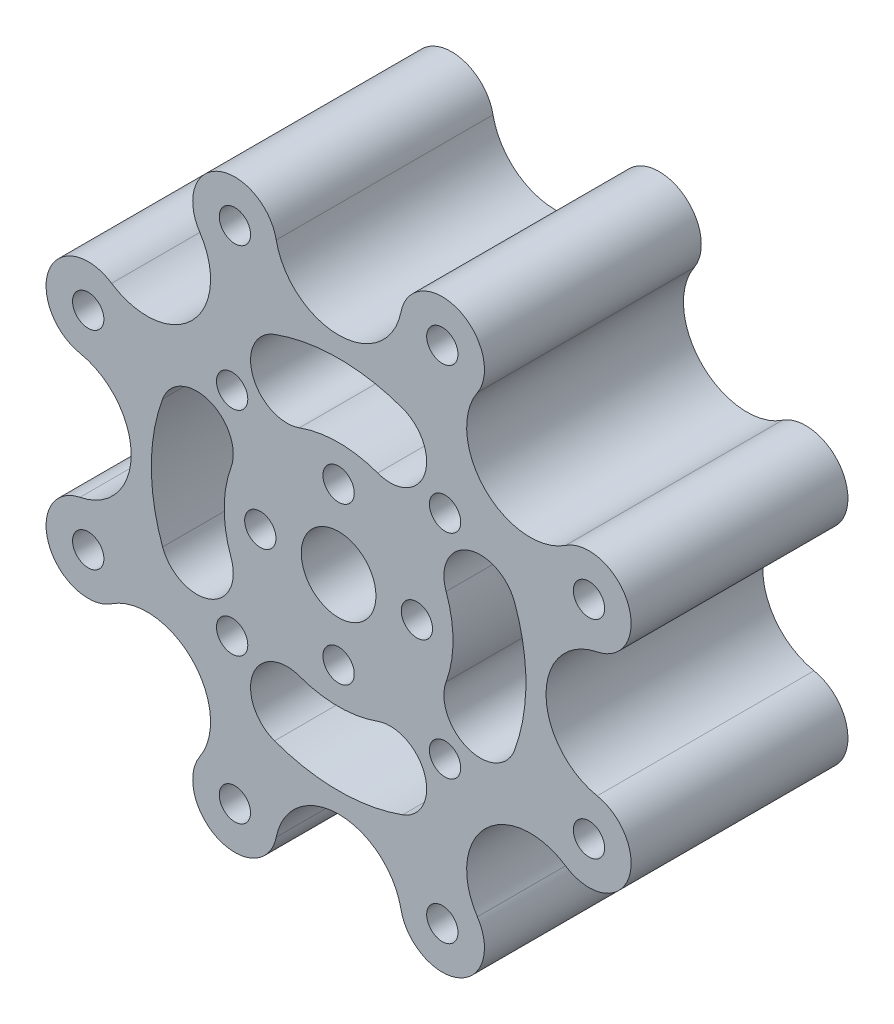
SolidWorks part; units mm, degrees
material "5052-H34"
ref_plane "正面" through (0, 0, 0) normal (0, 0, 1) x (1, 0, 0)
ref_plane "平面" through (0, 0, 0) normal (0, 1, 0) x (1, 0, 0)
ref_plane "右側面" through (0, 0, 0) normal (1, 0, 0) x (0, 0, -1)
sketch "ｽｹｯﾁ1" plane through (0, 0, 0) normal (0, 0, 1) x (1, 0, 0)
  line L0 (0, 27.5) -> (0, 0) construction
  line L1 (0, 0) -> (8.6104, 20.7873) construction
  line L3 (-8.8388, 8.8388) -> (8.8388, 8.8388) construction
  line L4 (-8.8388, 8.8388) -> (-8.8388, -8.8388) construction
  line L5 (-8.8388, -8.8388) -> (8.8388, -8.8388) construction
  line L6 (8.8388, 8.8388) -> (8.8388, -8.8388) construction
  line L7 (-8.8388, 8.8388) -> (8.8388, -8.8388) construction
  line L8 (-8.8388, -8.8388) -> (8.8388, 8.8388) construction
  circle A0 centre (0, 0) radius 27.5
  circle A1 centre (0, 0) radius 22.5 construction
  circle A2 centre (8.6104, 20.7873) radius 1.3
  arc A3 (11.5205, 18.8428) -> (5.1776, 21.4701) centre (8.6104, 20.7873) ccw
  arc A4 (-5.1776, 21.4701) -> (5.1776, 21.4701) centre (0, 22.5) ccw
  circle A5 centre (20.7873, 8.6104) radius 1.3
  circle A6 centre (20.7873, -8.6104) radius 1.3
  circle A7 centre (8.6104, -20.7873) radius 1.3
  circle A8 centre (-8.6104, -20.7873) radius 1.3
  circle A9 centre (-20.7873, -8.6104) radius 1.3
  circle A10 centre (-20.7873, 8.6104) radius 1.3
  circle A11 centre (-8.6104, 20.7873) radius 1.3
  arc A12 (-5.2824, 21.8711) -> (-11.73, 19.2005) centre (-8.6104, 20.7873) ccw construction
  arc A13 (5.2426, 21.8807) -> (0, 27.7791) centre (0, 22.5) ccw construction
  arc A14 (0, 27.7791) -> (-5.2426, 21.8807) centre (0, 22.5) ccw construction
  arc A15 (5.1776, 21.4701) -> (7.271, 17.5537) centre (8.6104, 20.7873) ccw construction
  arc A16 (19.1791, 11.7649) -> (11.5205, 18.8428) centre (15.9099, 15.9099) cw construction
  arc A17 (-5.2426, 21.8807) -> (-5.1776, 21.4701) centre (0, 22.5) ccw construction
  arc A18 (-5.1776, 21.4701) -> (-5.2824, 21.8711) centre (-8.6104, 20.7873) ccw construction
  arc A19 (5.1776, 21.4701) -> (5.2426, 21.8807) centre (0, 22.5) ccw construction
  arc A20 (7.271, 17.5537) -> (11.5205, 18.8428) centre (8.6104, 20.7873) ccw construction
  arc A21 (11.5205, 18.8428) -> (11.7649, 19.1791) centre (15.9099, 15.9099) cw construction
  arc A22 (-11.73, 19.2005) -> (-5.1776, 21.4701) centre (-8.6104, 20.7873) ccw construction
  arc A23 (11.5205, 18.8428) -> (18.8428, 11.5205) centre (15.9099, 15.9099) ccw
  arc A24 (21.4701, 5.1776) -> (18.8428, 11.5205) centre (20.7873, 8.6104) ccw
  arc A25 (21.4701, 5.1776) -> (21.4701, -5.1776) centre (22.5, 0) ccw
  arc A26 (18.8428, -11.5205) -> (21.4701, -5.1776) centre (20.7873, -8.6104) ccw
  arc A27 (18.8428, -11.5205) -> (11.5205, -18.8428) centre (15.9099, -15.9099) ccw
  arc A28 (5.1776, -21.4701) -> (11.5205, -18.8428) centre (8.6104, -20.7873) ccw
  arc A29 (5.1776, -21.4701) -> (-5.1776, -21.4701) centre (0, -22.5) ccw
  arc A30 (-11.5205, -18.8428) -> (-5.1776, -21.4701) centre (-8.6104, -20.7873) ccw
  arc A31 (-11.5205, -18.8428) -> (-18.8428, -11.5205) centre (-15.9099, -15.9099) ccw
  arc A32 (-21.4701, -5.1776) -> (-18.8428, -11.5205) centre (-20.7873, -8.6104) ccw
  arc A33 (-21.4701, -5.1776) -> (-21.4701, 5.1776) centre (-22.5, 0) ccw
  arc A34 (-18.8428, 11.5205) -> (-21.4701, 5.1776) centre (-20.7873, 8.6104) ccw
  arc A35 (-18.8428, 11.5205) -> (-11.5205, 18.8428) centre (-15.9099, 15.9099) ccw
  arc A36 (-5.1776, 21.4701) -> (-11.5205, 18.8428) centre (-8.6104, 20.7873) ccw
  circle A37 centre (8.8388, 8.8388) radius 1.3
  circle A38 centre (8.8388, -8.8388) radius 1.3
  circle A39 centre (-8.8388, -8.8388) radius 1.3
  circle A40 centre (-8.8388, 8.8388) radius 1.3
  circle A41 centre (0, 0) radius 6.5 construction
  circle A42 centre (0, 6.5) radius 1.3
  circle A43 centre (6.5, 0) radius 1.3
  circle A44 centre (0, -6.5) radius 1.3
  circle A45 centre (-6.5, 0) radius 1.3
  circle A46 centre (0, 0) radius 12.5 construction
  circle A47 centre (0, 12.5) radius 3 construction
  circle A48 centre (12.5, 0) radius 3 construction
  circle A49 centre (0, -12.5) radius 3 construction
  circle A50 centre (-12.5, 0) radius 3 construction
  circle A51 centre (0, 0) radius 3.1
  dimension "D1" = 55
  dimension "D2" = 45
  dimension "D4" = 2.6
  dimension "D6" = 2.6
  dimension "D7" = 13
  dimension "D9" = 6
  dimension "D10" = 25
  dimension "D12" = 3.5
  dimension "D13" = 6.2
  dimension "D3" = 22.5
  dimension "D5" = 25
  dimension "D11" = 8
  dimension "D8" = 4
  dimension "D14" = 4
extrude "ﾎﾞｽ - 押し出し1" add sketch "ｽｹｯﾁ1" along normal blind 18 contours A4 A36 A35 A34 A33 A32 A31 A30 A29 A28 A27 A26 A25 A24 A23 A3 A50 A49 A48 A47 A45 A44 A43 A42 A40 A39 A38 A37 A2 A5 A6 A7 A8
sketch "ｽｹｯﾁ2" plane through (0, 0, 18) normal (0, 0, 1) x (1, 0, 0)
  line L0 (0, 0) -> (4.2838, 11.7697) construction
  line L1 (0, 12.5) -> (0, 0) construction
  arc A0 (3.2492, 8.9271) -> (-3.2492, 8.9271) centre (0, 0) ccw
  arc A3 (5.3184, 14.6122) -> (-5.3184, 14.6122) centre (0, 0) ccw
  arc A4 (3.2492, 8.9271) -> (5.3184, 14.6122) centre (4.2838, 11.7697) ccw
  arc A5 (-3.2492, 8.9271) -> (-5.3184, 14.6122) centre (-4.2838, 11.7697) cw
  arc A6 (8.9271, 3.2492) -> (14.6122, 5.3184) centre (11.7697, 4.2838) cw
  arc A7 (14.6122, -5.3184) -> (14.6122, 5.3184) centre (0, 0) ccw
  arc A8 (8.9271, -3.2492) -> (8.9271, 3.2492) centre (0, 0) ccw
  arc A9 (8.9271, -3.2492) -> (14.6122, -5.3184) centre (11.7697, -4.2838) ccw
  arc A10 (3.2492, -8.9271) -> (5.3184, -14.6122) centre (4.2838, -11.7697) cw
  arc A11 (-5.3184, -14.6122) -> (5.3184, -14.6122) centre (0, 0) ccw
  arc A12 (-3.2492, -8.9271) -> (3.2492, -8.9271) centre (0, 0) ccw
  arc A13 (-3.2492, -8.9271) -> (-5.3184, -14.6122) centre (-4.2838, -11.7697) ccw
  arc A14 (-8.9271, -3.2492) -> (-14.6122, -5.3184) centre (-11.7697, -4.2838) cw
  arc A15 (-14.6122, 5.3184) -> (-14.6122, -5.3184) centre (0, 0) ccw
  arc A16 (-8.9271, 3.2492) -> (-8.9271, -3.2492) centre (0, 0) ccw
  arc A17 (-8.9271, 3.2492) -> (-14.6122, 5.3184) centre (-11.7697, 4.2838) ccw
  dimension "D4" = 6.05
  dimension "D1" = 20
  dimension "D3" = 12.5
  dimension "D5" = 9.5
  dimension "D2" = 4
extrude "ｶｯﾄ - 押し出し1" cut sketch "ｽｹｯﾁ2" against normal through all
